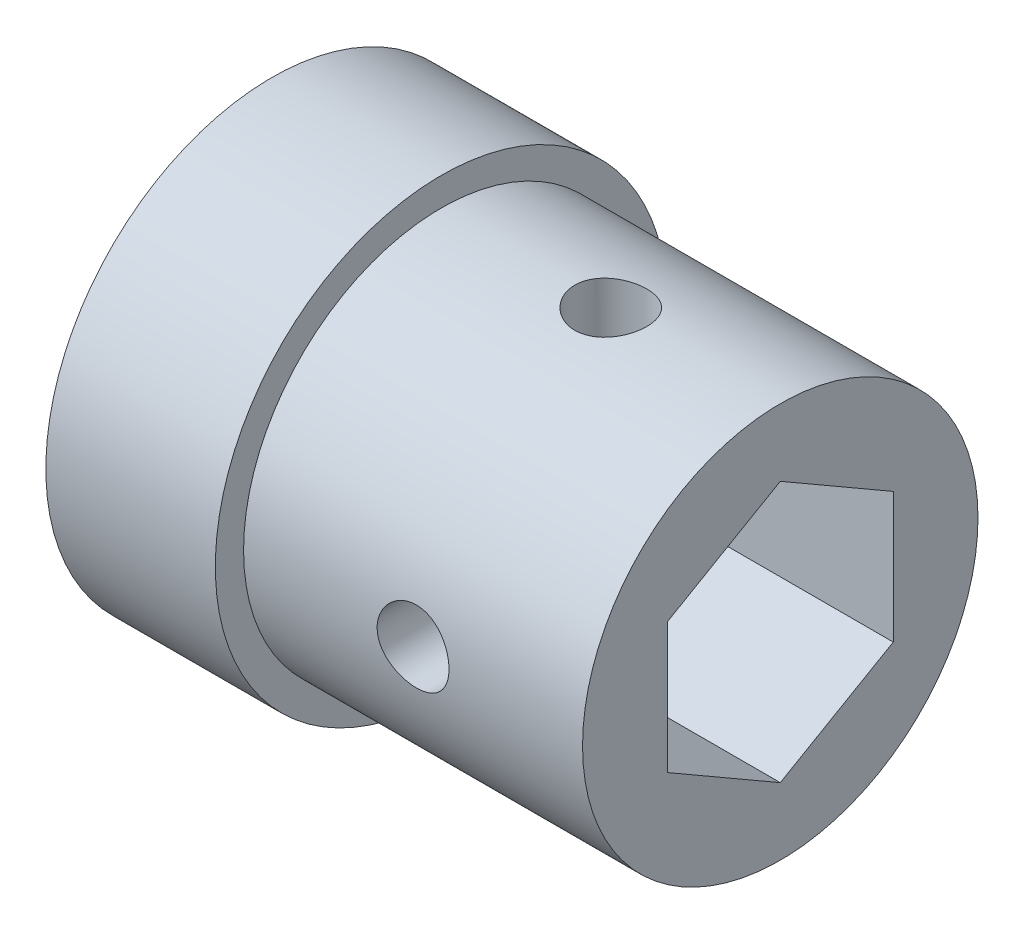
SolidWorks part; units mm, degrees
material "6061-T6 (SS)"
ref_plane "Front Plane" through (0, 0, 0) normal (0, 0, 1) x (1, 0, 0)
ref_plane "Top Plane" through (0, 0, 0) normal (0, 1, 0) x (1, 0, 0)
ref_plane "Right Plane" through (0, 0, 0) normal (1, 0, 0) x (0, 0, -1)
sketch "Sketch1" plane through (0, 0, 0) normal (1, 0, 0) x (0, 0, -1)
  circle A0 centre (0, 0) radius 11.1125
  dimension "D1" = 22.225
extrude "Boss-Extrude1" add sketch "Sketch1" along normal blind 19.05
sketch "Sketch2" plane through (0, 0, 0) normal (-1, 0, 0) x (0, 0, 1)
  circle A0 centre (0, 0) radius 12.7
  dimension "D1" = 25.4
extrude "Boss-Extrude2" add sketch "Sketch2" along normal blind 9.525
sketch "Sketch3" plane through (-9.525, 0, 0) normal (-1, 0, 0) x (0, 0, 1)
  circle A0 centre (0, 0) radius 11.1125
  dimension "D1" = 22.225
sketch "Sketch4" plane through (-9.525, 0, 0) normal (-1, 0, 0) x (0, 0, 1)
  line L1 (0, 7.3323) -> (-6.35, 3.6662)
  line L2 (-6.35, 3.6662) -> (-6.35, -3.6662)
  line L3 (-6.35, -3.6662) -> (0, -7.3323)
  line L4 (0, -7.3323) -> (6.35, -3.6662)
  line L5 (6.35, -3.6662) -> (6.35, 3.6662)
  line L6 (6.35, 3.6662) -> (0, 7.3323)
  circle A0 centre (0, 0) radius 6.35 construction
  dimension "D1" = 12.7
extrude "Cut-Extrude1" cut sketch "Sketch4" against normal through all
sketch "Sketch5" plane through (0, 0, 0) normal (0, 0, 1) x (1, 0, 0)
  circle A0 centre (9.525, 0) radius 2.0193
  dimension "D1" = 4.0386
  dimension "D2" = 9.525
extrude "Cut-Extrude2" cut sketch "Sketch5" against normal through all both and the other way through all
sketch "Sketch6" plane through (0, 0, 0) normal (0, 1, 0) x (1, 0, 0)
  circle A0 centre (9.525, 0) radius 2.0193
  dimension "D1" = 4.0386
  dimension "D2" = 9.525
extrude "Cut-Extrude3" cut sketch "Sketch6" against normal through all both and the other way through all
sketch "Sketch7" plane through (19.05, 0, 0) normal (1, 0, 0) x (0, 0, -1)
  line L0 (4.7625, -7.9375) -> (-4.7625, -7.9375)
  line L1 (7.9375, 4.7625) -> (12.6365, 4.7625)
  line L2 (7.9375, 4.7625) -> (7.9375, -4.7625)
  line L3 (7.9375, -4.7625) -> (12.6365, -4.7625)
  line L4 (12.6365, 4.7625) -> (12.6365, -4.7625)
  line L5 (4.7625, -7.9375) -> (4.7625, -12.6365)
  line L6 (4.7625, -12.6365) -> (-4.7625, -12.6365)
  line L7 (-4.7625, -7.9375) -> (-4.7625, -12.6365)
  line L8 (-7.9375, -4.7625) -> (-7.9375, 4.7625)
  line L9 (-7.9375, -4.7625) -> (-12.6365, -4.7625)
  line L10 (-12.6365, -4.7625) -> (-12.6365, 4.7625)
  line L11 (-7.9375, 4.7625) -> (-12.6365, 4.7625)
  line L12 (-4.7625, 7.9375) -> (4.7625, 7.9375)
  line L13 (-4.7625, 7.9375) -> (-4.7625, 12.6365)
  line L14 (-4.7625, 12.6365) -> (4.7625, 12.6365)
  line L15 (4.7625, 7.9375) -> (4.7625, 12.6365)
  point P4 (12.6365, 0)
  point P21 (0, 0)
  dimension "D1" = 4.699
  dimension "D2" = 9.525
  dimension "D3" = 7.9375
  dimension "D4" = 4
